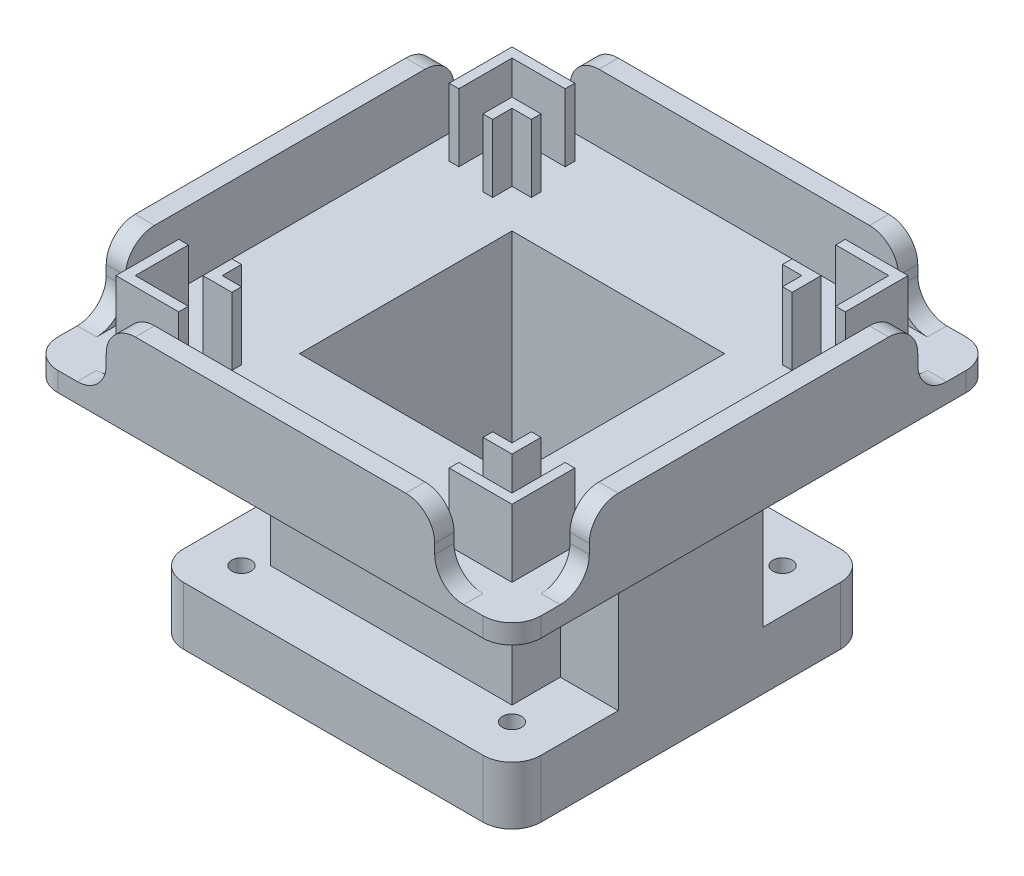
SolidWorks part; units mm, degrees
ref_plane "前视基准面" through (0, 0, 0) normal (0, 0, 1) x (1, 0, 0)
ref_plane "上视基准面" through (0, 0, 0) normal (0, 1, 0) x (1, 0, 0)
ref_plane "右视基准面" through (0, 0, 0) normal (1, 0, 0) x (0, 0, -1)
sketch "草图2" plane through (0, 0, 0) normal (0, 1, 0) x (1, 0, 0)
  line L1 (18.5, -18.5) -> (-18.5, -18.5)
  line L2 (18.5, -18.5) -> (18.5, 18.5)
  line L3 (18.5, 18.5) -> (-18.5, 18.5)
  line L4 (-18.5, -18.5) -> (-18.5, 18.5)
  line L5 (18.5, -18.5) -> (-18.5, 18.5) construction
  line L6 (18.5, 18.5) -> (-18.5, -18.5) construction
  point P0 (0, 0)
  dimension "D1" = 37
  dimension "D2" = 37
extrude "凸台-拉伸1" add sketch "草图2" along normal blind 23
sketch "草图3" plane through (0, 0, 0) normal (0, -1, 0) x (1, 0, 0)
  line L1 (11, -11) -> (-11, -11)
  line L2 (11, -11) -> (11, 11)
  line L3 (11, 11) -> (-11, 11)
  line L4 (-11, -11) -> (-11, 11)
  line L5 (11, -11) -> (-11, 11) construction
  line L6 (11, 11) -> (-11, -11) construction
  point P1 (0, 0)
  dimension "D1" = 22
  dimension "D2" = 22
extrude "切除-拉伸1" cut sketch "草图3" against normal blind 23
sketch3d "3D草图1" plane through (0, 0, 0) normal (0, 0, 1) x (1, 0, 0)
  dimension "D1" = 6
sketch "草图19" plane through (0, 6, 0) normal (0, -1, 0) x (-1, 0, 0)
  line L1 (-12.5, -12.5) -> (12.5, -12.5)
  line L2 (-12.5, -12.5) -> (-12.5, 12.5)
  line L3 (-12.5, 12.5) -> (12.5, 12.5)
  line L4 (12.5, -12.5) -> (12.5, 12.5)
  line L5 (-12.5, -12.5) -> (12.5, 12.5) construction
  line L6 (-12.5, 12.5) -> (12.5, -12.5) construction
  point P0 (0, 0)
  dimension "D1" = 25
  dimension "D2" = 25
extrude "切除-拉伸17" cut sketch "草图19" against normal blind 17 flip side to cut
sketch "草图4" plane through (0, 23, 0) normal (0, 1, 0) x (1, 0, 0)
  line L1 (25, 25) -> (-25, 25)
  line L2 (25, 25) -> (25, -25)
  line L3 (25, -25) -> (-25, -25)
  line L4 (-25, 25) -> (-25, -25)
  line L5 (25, 25) -> (-25, -25) construction
  line L6 (25, -25) -> (-25, 25) construction
  point P0 (0, 0)
  dimension "D1" = 50
  dimension "D2" = 50
extrude "凸台-拉伸2" add sketch "草图4" along normal blind 9
sketch "草图5" plane through (0, 32, 0) normal (0, 1, 0) x (1, 0, 0)
  line L1 (23, 23) -> (-23, 23)
  line L2 (23, 23) -> (23, -23)
  line L3 (23, -23) -> (-23, -23)
  line L4 (-23, 23) -> (-23, -23)
  line L5 (23, 23) -> (-23, -23) construction
  line L6 (23, -23) -> (-23, 23) construction
  point P0 (0, 0)
  dimension "D1" = 46
  dimension "D2" = 46
extrude "切除-拉伸3" cut sketch "草图5" against normal blind 7
sketch "草图12" plane through (0, 25, 0) normal (0, 1, 0) x (1, 0, 0)
  line L0 (-25, 25) -> (-25, -25) construction
  line L1 (-17, -17) -> (-25, -17)
  line L2 (-17, -17) -> (-17, -25)
  line L3 (-17, -25) -> (-25, -25)
  line L4 (-25, -17) -> (-25, -25)
  line L5 (-25, -25) -> (25, -25) construction
  line L6 (-17, 17) -> (-25, 17)
  line L7 (-17, 17) -> (-17, 25)
  line L8 (-17, 25) -> (-25, 25)
  line L9 (-25, 17) -> (-25, 25)
  line L10 (17, 17) -> (17, 25)
  line L11 (17, 17) -> (25, 17)
  line L12 (25, 17) -> (25, 25)
  line L13 (17, 25) -> (25, 25)
  line L14 (17, -17) -> (25, -17)
  line L15 (17, -17) -> (17, -25)
  line L16 (17, -25) -> (25, -25)
  line L17 (25, -17) -> (25, -25)
  dimension "D1" = 0
  dimension "D2" = 0
  dimension "D3" = 8
  dimension "D4" = 8
  dimension "D5" = 4
extrude "切除-拉伸14" cut sketch "草图12" along normal blind 14
sketch "草图6" plane through (0, 25, 0) normal (0, 1, 0) x (1, 0, 0)
  line L1 (11, 11) -> (-11, 11)
  line L2 (11, 11) -> (11, -11)
  line L3 (11, -11) -> (-11, -11)
  line L4 (-11, 11) -> (-11, -11)
  line L5 (11, 11) -> (-11, -11) construction
  line L6 (11, -11) -> (-11, 11) construction
  point P0 (0, 0)
  dimension "D1" = 22
  dimension "D2" = 22
extrude "切除-拉伸4" cut sketch "草图6" against normal blind 2
sketch "草图11" plane through (0, 0, 0) normal (0, -1, 0) x (1, 0, 0)
  line L0 (18.5, 18.5) -> (18.5, -18.5) construction
  line L1 (-18.5, 18.5) -> (18.5, 18.5) construction
  circle A0 centre (14, 14) radius 1
  circle A1 centre (14, -14) radius 1
  circle A2 centre (-14, -14) radius 1
  circle A3 centre (-14, 14) radius 1
  dimension "D1" = 4.5
  dimension "D3" = 2
  dimension "D2" = 4.5
  dimension "D4" = 4
extrude "切除-拉伸7" cut sketch "草图11" against normal blind 8
sketch "草图13" plane through (0, 25, 0) normal (0, 1, 0) x (1, 0, 0)
  line L1 (-20.5, 20.5) -> (20.5, 20.5)
  line L2 (-20.5, 20.5) -> (-20.5, -20.5)
  line L3 (-20.5, -20.5) -> (20.5, -20.5)
  line L4 (20.5, 20.5) -> (20.5, -20.5)
  line L5 (-20.5, 20.5) -> (20.5, -20.5) construction
  line L6 (-20.5, -20.5) -> (20.5, 20.5) construction
  line L7 (-19.5, 19.5) -> (19.5, 19.5)
  line L8 (-19.5, 19.5) -> (-19.5, -19.5)
  line L9 (-19.5, -19.5) -> (19.5, -19.5)
  line L10 (19.5, 19.5) -> (19.5, -19.5)
  line L11 (-19.5, 19.5) -> (19.5, -19.5) construction
  line L12 (-19.5, -19.5) -> (19.5, 19.5) construction
  point P0 (0, 0)
  point P6 (0, 0)
  dimension "D1" = 41
  dimension "D2" = 41
  dimension "D3" = 39
  dimension "D4" = 39
extrude "凸台-拉伸3" add sketch "草图13" along normal blind 7
sketch "草图17" plane through (0, 25, 0) normal (0, 1, 0) x (1, 0, 0)
  line L1 (15, -15) -> (-15, -15)
  line L2 (15, -15) -> (15, 15)
  line L3 (15, 15) -> (-15, 15)
  line L4 (-15, -15) -> (-15, 15)
  line L5 (15, -15) -> (-15, 15) construction
  line L6 (15, 15) -> (-15, -15) construction
  line L7 (16, -16) -> (-16, -16)
  line L8 (16, -16) -> (16, 16)
  line L9 (16, 16) -> (-16, 16)
  line L10 (-16, -16) -> (-16, 16)
  line L11 (16, -16) -> (-16, 16) construction
  line L12 (16, 16) -> (-16, -16) construction
  point P0 (0, 0)
  point P6 (0, 0)
  dimension "D1" = 30
  dimension "D2" = 30
  dimension "D3" = 32
  dimension "D4" = 32
extrude "凸台-拉伸4" add sketch "草图17" along normal blind 7
sketch "草图15" plane through (0, 25, 0) normal (0, 1, 0) x (1, 0, 0)
  line L0 (-14, -19.5) -> (-14, -20.5)
  line L1 (19.5, 14) -> (20.5, 14)
  line L2 (19.5, 14) -> (19.5, -14)
  line L3 (19.5, -14) -> (20.5, -14)
  line L4 (20.5, 14) -> (20.5, -14)
  line L5 (19.5, 14) -> (20.5, -14) construction
  line L6 (19.5, -14) -> (20.5, 14) construction
  line L7 (20.5, -20.5) -> (20.5, 20.5) construction
  line L8 (14, -20.5) -> (-14, -20.5)
  line L9 (19.5, -19.5) -> (19.5, 19.5) construction
  line L10 (14, -19.5) -> (-14, -19.5)
  line L11 (14, -19.5) -> (14, -20.5)
  line L12 (-19.5, 14) -> (-20.5, 14)
  line L13 (-20.5, -14) -> (-20.5, 14)
  line L14 (-19.5, -14) -> (-19.5, 14)
  line L15 (-19.5, -14) -> (-20.5, -14)
  line L16 (14, 19.5) -> (14, 20.5)
  line L17 (-14, 20.5) -> (14, 20.5)
  line L18 (-14, 19.5) -> (14, 19.5)
  line L19 (-14, 19.5) -> (-14, 20.5)
  point P0 (20, 0)
  point P5 (20.5, 0)
  point P6 (19.5, 0)
  point P11 (19.5, 0)
  dimension "D1" = 0
  dimension "D2" = 1
  dimension "D3" = 0
  dimension "D4" = 28
  dimension "D5" = 4
extrude "切除-拉伸15" cut sketch "草图15" along normal blind 7
sketch "草图18" plane through (0, 25, 0) normal (0, 1, 0) x (1, 0, 0)
  line L0 (15, -15) -> (15, 15) construction
  line L1 (16, -13) -> (15, -13)
  line L2 (16, -13) -> (16, 13)
  line L3 (16, 13) -> (15, 13)
  line L4 (15, -13) -> (15, 13)
  line L5 (16, -13) -> (15, 13) construction
  line L6 (16, 13) -> (15, -13) construction
  line L7 (16, -16) -> (16, 16) construction
  line L32 (-13, -16) -> (13, -16)
  line L33 (13, -16) -> (13, -15)
  line L34 (-13, -15) -> (13, -15)
  line L35 (-13, -16) -> (-13, -15)
  line L36 (-16, 13) -> (-16, -13)
  line L37 (-16, -13) -> (-15, -13)
  line L38 (-15, 13) -> (-15, -13)
  line L39 (-16, 13) -> (-15, 13)
  line L40 (13, 16) -> (-13, 16)
  line L41 (-13, 16) -> (-13, 15)
  line L42 (13, 15) -> (-13, 15)
  line L43 (13, 16) -> (13, 15)
  line L44 (0, 0) -> (15, -13) construction
  point P0 (15.5, 0)
  point P7 (16, 0)
  point P10 (16, 0)
  dimension "D1" = 0
  dimension "D2" = 1
  dimension "D3" = 0
  dimension "D4" = 26
  dimension "D5" = 4
  dimension "D6" = 19.8494
extrude "切除-拉伸16" cut sketch "草图18" along normal blind 7
sketch "草图20" plane through (0, 0, 0) normal (0, -1, 0) x (1, 0, 0)
  line L0 (-11, -11) -> (11, -11) construction
  line L1 (11, 0) -> (14, 0)
  line L2 (11, 0) -> (11, -10.5)
  line L3 (11, -10.5) -> (14, -10.5)
  line L4 (14, 0) -> (14, -10.5)
  line L5 (11, 0) -> (14, -10.5) construction
  line L6 (11, -10.5) -> (14, 0) construction
  line L7 (11, -11) -> (11, 11) construction
  point P0 (12.5, -5.25)
  dimension "D1" = 0.5
  dimension "D2" = 0
  dimension "D3" = 3
  dimension "D4" = 10.5
extrude "切除-拉伸18" cut sketch "草图20" against normal blind 3.5
sketch "草图21" plane through (0, 0, 0) normal (0, -1, 0) x (1, 0, 0)
  line L0 (-11, -11) -> (11, -11) construction
  line L1 (-11, -7) -> (-15.5, -7)
  line L2 (-11, -7) -> (-11, 3)
  line L3 (-11, 3) -> (-15.5, 3)
  line L4 (-15.5, -7) -> (-15.5, 3)
  line L5 (-11, -7) -> (-15.5, 3) construction
  line L6 (-11, 3) -> (-15.5, -7) construction
  line L7 (-11, 11) -> (-11, -11) construction
  point P0 (-13.25, -2)
  dimension "D1" = 4
  dimension "D2" = 10
  dimension "D3" = 0
  dimension "D4" = 4.5
extrude "切除-拉伸19" cut sketch "草图21" against normal blind 1
sketch "草图22" plane through (0, 0, 0) normal (0, -1, 0) x (1, 0, 0)
  line L1 (-2.5, -11) -> (2.5, -11)
  line L2 (-2.5, -11) -> (-2.5, -12)
  line L3 (-2.5, -12) -> (2.5, -12)
  line L4 (2.5, -11) -> (2.5, -12)
  line L5 (-2.5, -11) -> (2.5, -12) construction
  line L6 (-2.5, -12) -> (2.5, -11) construction
  line L7 (-11, -11) -> (11, -11) construction
  line L11 (0, 0) -> (7.3651, 0) construction
  line L13 (-2.5, 12) -> (2.5, 12)
  line L14 (2.5, 11) -> (2.5, 12)
  line L15 (-2.5, 11) -> (2.5, 11)
  line L16 (-2.5, 11) -> (-2.5, 12)
  point P0 (0, -11.5)
  point P7 (0, -11)
  point P8 (0, -11)
  point P9 (-2.5, -11.5)
  dimension "D1" = 1
  dimension "D2" = 0
  dimension "D3" = 0
  dimension "D4" = 5
extrude "切除-拉伸21" cut sketch "草图22" against normal blind 7
sketch "草图24" plane through (0, 0, 0) normal (0, -1, 0) x (1, 0, 0)
  line L0 (-11, -11) -> (-2.5, -11) construction
  line L1 (-1.5, -11) -> (-7.5, -11)
  line L2 (-1.5, -11) -> (-1.5, -15.5)
  line L3 (-1.5, -15.5) -> (-7.5, -15.5)
  line L4 (-7.5, -11) -> (-7.5, -15.5)
  line L5 (-1.5, -11) -> (-7.5, -15.5) construction
  line L6 (-1.5, -15.5) -> (-7.5, -11) construction
  line L7 (-11, -7) -> (-11, -11) construction
  point P0 (-4.5, -13.25)
  dimension "D1" = 0
  dimension "D2" = 3.5
  dimension "D3" = 4.5
  dimension "D4" = 6
extrude "切除-拉伸22" cut sketch "草图24" against normal blind 1
sketch "草图25" plane through (0, 6, 0) normal (0, 1, 0) x (1, 0, 0)
  line L0 (18.5, 18.5) -> (18.5, -18.5) construction
  line L1 (18.5, 7.5) -> (12.5, 7.5)
  line L2 (18.5, 7.5) -> (18.5, -7.5)
  line L3 (18.5, -7.5) -> (12.5, -7.5)
  line L4 (12.5, 7.5) -> (12.5, -7.5)
  line L5 (18.5, 7.5) -> (12.5, -7.5) construction
  line L6 (18.5, -7.5) -> (12.5, 7.5) construction
  line L7 (12.5, 12.5) -> (12.5, -12.5) construction
  point P0 (15.5, 0)
  point P9 (15.5, -7.5)
  point P10 (18.5, 0)
  point P11 (18.5, 0)
  dimension "D1" = 0
  dimension "D2" = 0
  dimension "D3" = 15
  dimension "D4" = 0
extrude "凸台-拉伸5" add sketch "草图25" along normal blind 17
sketch "草图26" plane through (18.5, 0, 0) normal (1, 0, 0) x (0, 0, -1)
  line L0 (-7.5, 23) -> (7.5, 23) construction
  line L1 (7.5, 20) -> (-7.5, 20)
  line L2 (7.5, 20) -> (7.5, 23)
  line L3 (7.5, 23) -> (-7.5, 23)
  line L4 (-7.5, 20) -> (-7.5, 23)
  line L5 (7.5, 20) -> (-7.5, 23) construction
  line L6 (7.5, 23) -> (-7.5, 20) construction
  line L7 (7.5, 23) -> (7.5, 6) construction
  line L8 (-7.5, 23) -> (-7.5, 6) construction
  point P0 (0, 21.5)
  dimension "D1" = 0
  dimension "D2" = 0
  dimension "D3" = 0
  dimension "D4" = 3
fillet "圆角5" radius 3 1 edges at (25, 24, -25)
fillet "圆角6" radius 3 1 edges at (25, 24, 25)
fillet "圆角10" radius 3 1 edges at (17, 25, -24)
fillet "圆角11" radius 3 1 edges at (24, 32, -17)
fillet "圆角12" radius 3 1 edges at (24, 25, -17)
fillet "圆角14" radius 3 1 edges at (17, 25, 24)
fillet "圆角15" radius 3 1 edges at (24, 32, 17)
fillet "圆角16" radius 3 1 edges at (24, 25, 17)
fillet "圆角19" radius 3 1 edges at (-18.5, 3, -18.5)
fillet "圆角20" radius 3 1 edges at (-18.5, 3, 18.5)
fillet "圆角21" radius 3 1 edges at (18.5, 3, 18.5)
fillet "圆角22" radius 3 1 edges at (18.5, 3, -18.5)
fillet "圆角28" radius 3 1 edges at (-17, 25, -24)
fillet "圆角29" radius 3 1 edges at (-24, 25, -17)
fillet "圆角30" radius 3 1 edges at (-24, 25, 17)
fillet "圆角31" radius 3 1 edges at (-17, 25, 24)
fillet "圆角32" radius 3 1 edges at (17, 32, 24)
fillet "圆角33" radius 3 1 edges at (-17, 32, 24)
fillet "圆角34" radius 3 1 edges at (17, 32, -24)
fillet "圆角35" radius 3 1 edges at (-17, 32, -24)
fillet "圆角36" radius 3 1 edges at (-24, 32, 17)
fillet "圆角37" radius 3 1 edges at (-24, 32, -17)
fillet "圆角38" radius 3 1 edges at (-25, 24, 25)
fillet "圆角39" radius 3 1 edges at (-25, 24, -25)
